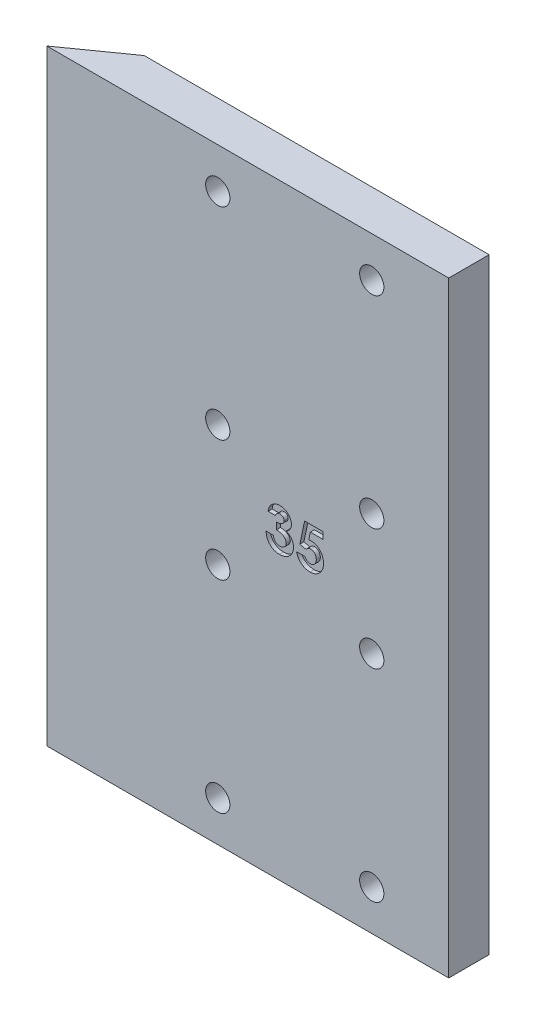
SolidWorks part; units mm, degrees
ref_plane "Front Plane" through (0, 0, 0) normal (0, 0, 1) x (1, 0, 0)
ref_plane "Top Plane" through (0, 0, 0) normal (0, 1, 0) x (1, 0, 0)
ref_plane "Right Plane" through (0, 0, 0) normal (1, 0, 0) x (0, 0, -1)
sketch "Sketch1" plane through (0, 0, 0) normal (0, 0, 1) x (1, 0, 0)
  line L0 (38.1, -469.9) -> (38.1, 469.9) construction
  line L1 (-38.1, -469.9) -> (-38.1, 469.9) construction
  line L2 (38.1, -75) -> (38.1, 75)
  line L3 (-38.1, -75) -> (-38.1, 75)
  line L6 (0, -75) -> (38.1, -75)
  line L7 (0, -75) -> (-38.1, -75)
  line L8 (0, 75) -> (38.1, 75)
  line L9 (0, 75) -> (-38.1, 75)
  circle A0 centre (19.05, 65) radius 3
  circle A1 centre (19.05, 15) radius 3
  circle A2 centre (-19.05, 15) radius 3
  circle A3 centre (-19.05, 65) radius 3
  circle A4 centre (19.05, -65) radius 3
  circle A5 centre (19.05, -15) radius 3
  circle A6 centre (-19.05, -15) radius 3
  circle A7 centre (-19.05, -65) radius 3
extrude "Boss-Extrude1" add sketch "Sketch1" along normal blind 10
sketch "Sketch2" plane through (0, -75, 0) normal (0, -1, 0) x (1, 0, 0)
  line L0 (-38.1, -6.4969) -> (-333.3108, 202.9981) construction
  line L1 (-38.1, 10) -> (-38.1, 0) construction
  line L2 (-47.2551, 0) -> (-61.3466, 10)
  line L3 (-38.1, 10) -> (-38.1, 0)
  line L4 (-38.1, 0) -> (-47.2551, 0)
  line L5 (-38.1, 10) -> (-61.3466, 10)
extrude "Boss-Extrude2" add sketch "Sketch2" against normal up to surface (150 mm away) up to face at (0, 75, 5)
sketch "Sketch3" plane through (0, 0, 10) normal (0, 0, 1) x (1, 0, 0)
  text T0 "35" font "Century Gothic" height 10
extrude "Cut-Extrude1" cut sketch "Sketch3" against normal blind 1
